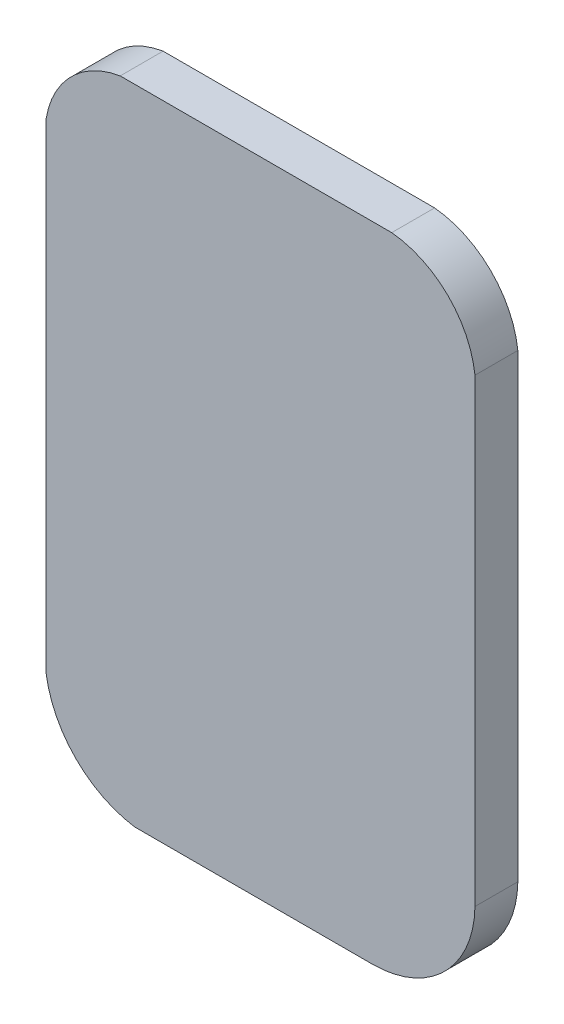
SolidWorks part; units mm, degrees
ref_plane "Front Plane" through (0, 0, 0) normal (0, 0, 1) x (1, 0, 0)
ref_plane "Top Plane" through (0, 0, 0) normal (0, 1, 0) x (1, 0, 0)
ref_plane "Right Plane" through (0, 0, 0) normal (1, 0, 0) x (0, 0, -1)
sketch "Sketch3" plane through (0, 0, 0) normal (0, 0, 1) x (1, 0, 0)
  line L1 (-392.7667, 900) -> (367.0477, 900)
  line L2 (-600, 692.7667) -> (-600, -652.2622)
  line L3 (-352.2622, -900) -> (316.6757, -900)
  line L4 (600, 671.0223) -> (600, -616.6757)
  arc A0 (-600, 692.7667) -> (-392.7667, 900) centre (-352.2622, 652.2622) cw
  arc A1 (600, 671.0223) -> (367.0477, 900) centre (341.8617, 641.39) ccw
  arc A2 (-352.2622, -900) -> (-600, -652.2622) centre (-307.9824, -607.9824) cw
  arc A3 (600, -607.9824) -> (316.6757, -900) centre (312.329, -612.329) cw
extrude "Boss-Extrude1" add sketch "Sketch3" along normal blind 120 contours A3 L4 A1 L1 A0 L2 A2 L3
